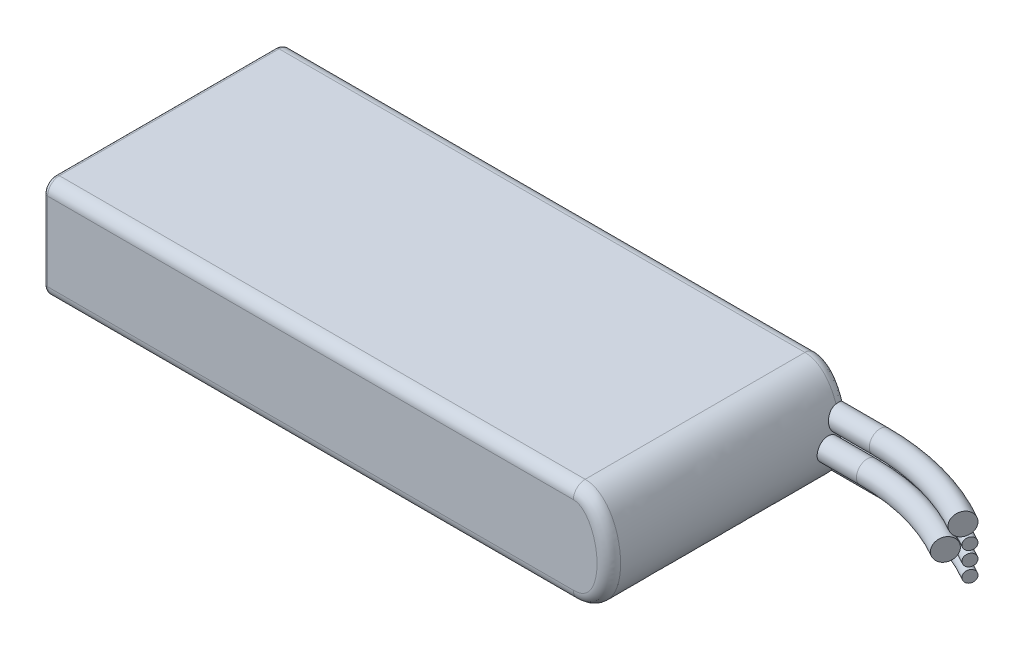
SolidWorks part; units mm, degrees
ref_plane "Plan de face" through (0, 0, 0) normal (0, 0, 1) x (1, 0, 0)
ref_plane "Plan de dessus" through (0, 0, 0) normal (0, 1, 0) x (1, 0, 0)
ref_plane "Plan de droite" through (0, 0, 0) normal (1, 0, 0) x (0, 0, -1)
sketch "Esquisse1" plane through (0, 0, 0) normal (0, 0, 1) x (1, 0, 0)
  line L0 (91.3075, 0) -> (81.7075, 0) construction
  line L1 (0, 0) -> (67.5, 0)
  line L2 (0, 0) -> (0, -13)
  line L3 (0, -13) -> (67.5, -13)
  line L4 (79.3737, -13) -> (93.6803, -13) construction
  line L5 (67.5, 0) -> (67.5, -13) construction
  line L6 (67.5, -6.5) -> (72, -6.5) construction
  spline S0 degree 3 poles (67.5, 0) (72.8199, 0) (74.1801, -13) (67.5, -13) knots 0 0 0 0 1 1 1 1
  dimension "D1" = 13
  dimension "D2" = 4.5
  dimension "D3" = 72
extrude "Boss.-Extru.1" add sketch "Esquisse1" along normal mid plane 31
fillet "Congé1" radius 1.5 6 edges at (33.75, -13, -15.5) (33.75, -13, 15.5) (33.75, 0, -15.5) (33.75, 0, 15.5)
fillet "Congé2" radius 0.5 8 edges at (0, -0.4393, -15.0607) (0, 0, 0) (0, -0.4393, 15.0607) (0, -6.5, 15.5) (0, -12.5607, 15.0607) (0, -13, 0) (0, -12.5607, -15.0607) (0, -6.5, -15.5)
sketch "Esquisse2" plane through (0, 0, 0) normal (1, 0, 0) x (0, 0, -1)
  line L0 (15.5, -11.5) -> (15.5, -1.5) construction
  line L1 (-14, -13) -> (14, -13) construction
  circle A0 centre (14.75, -11) radius 0.75
  circle A1 centre (14.75, -9.2) radius 0.75
  circle A2 centre (14.75, -7.4) radius 0.75
  circle A3 centre (14.1, -5.1) radius 1.4
  circle A4 centre (12.4598, -7.6119) radius 1.4
  dimension "D1" = 1.5
  dimension "D2" = 2.8
  dimension "D3" = 1.8
  dimension "D4" = 1.8
  dimension "D5" = 2.3
  dimension "D6" = 3
  dimension "D7" = 2.3
  dimension "D8" = 2
extrude "Boss.-Extru.2" add sketch "Esquisse2" along normal blind 75 from offset 2
sketch "Esquisse3" plane through (77, 0, 0) normal (1, 0, 0) x (0, 0, -1)
  line L0 (-14.7064, 3.3934) -> (-14.7064, -14.183) construction
  circle A1 centre (12.4598, -7.6119) radius 1.4
  circle A2 centre (12.4598, -7.6119) radius 1.4
  circle A3 centre (14.1, -5.1) radius 1.4
  circle A4 centre (14.1, -5.1) radius 1.4
  circle A5 centre (14.75, -7.4) radius 0.75
  circle A6 centre (14.75, -7.4) radius 0.75
  circle A7 centre (14.75, -9.2) radius 0.75
  circle A8 centre (14.75, -9.2) radius 0.75
  circle A9 centre (14.75, -11) radius 0.75
  circle A10 centre (14.75, -11) radius 0.75
  dimension "D1" = 0
  dimension "D2" = 0
  dimension "D3" = 0
  dimension "D4" = 0
  dimension "D5" = 0
revolve "Révolution1" add sketch "Esquisse3" angle 30 about L0
